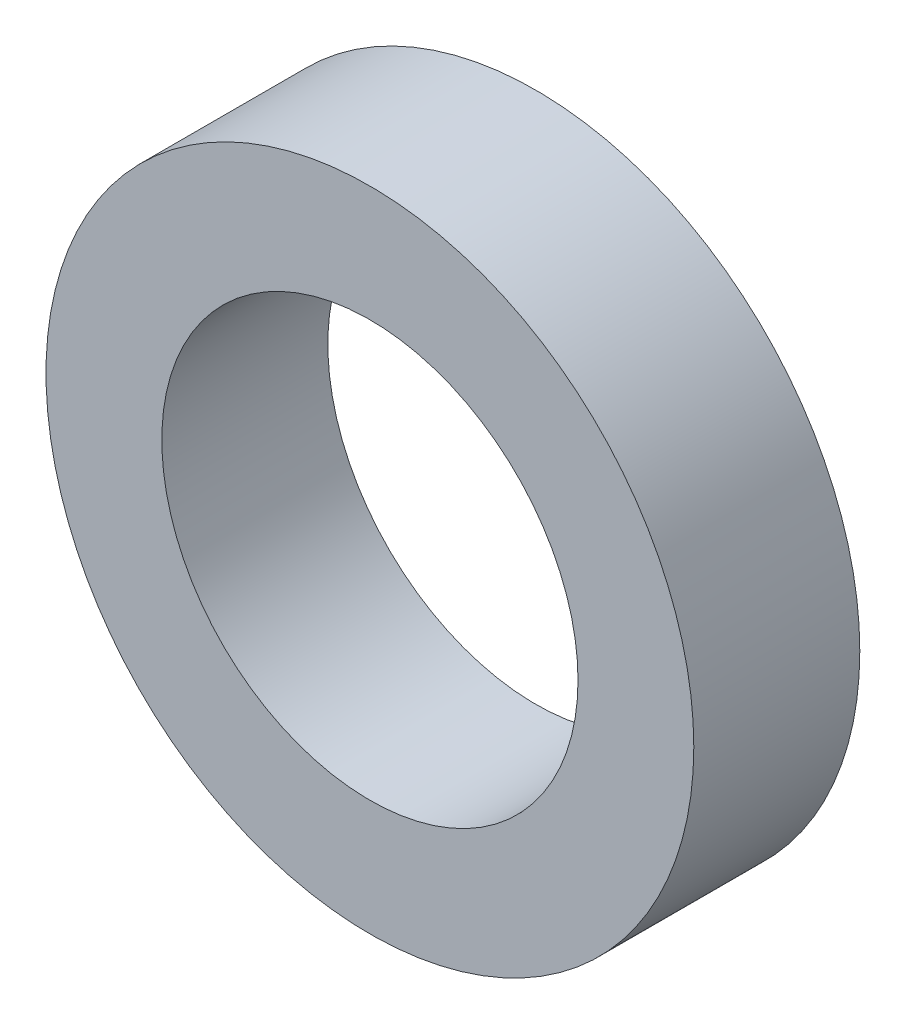
SolidWorks part; units mm, degrees
ref_plane "Front Plane" through (0, 0, 0) normal (0, 0, 1) x (1, 0, 0)
ref_plane "Top Plane" through (0, 0, 0) normal (0, 1, 0) x (1, 0, 0)
ref_plane "Right Plane" through (0, 0, 0) normal (1, 0, 0) x (0, 0, -1)
sketch "Sketch1" plane through (0, 0, 0) normal (0, 0, 1) x (1, 0, 0)
  circle A0 centre (0, 0) radius 3.2639
  circle A1 centre (0, 0) radius 5.08
  dimension "D1" = 6.5278
  dimension "D2" = 10.16
extrude "Boss-Extrude1" add sketch "Sketch1" along normal blind 2.6035
